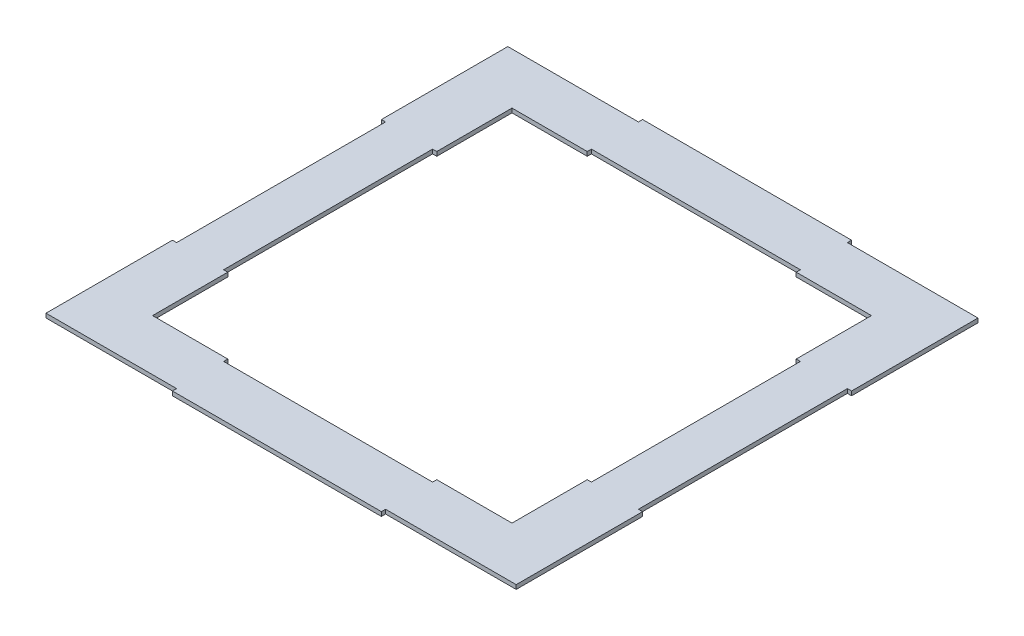
SolidWorks part; units mm, degrees
ref_plane "Front Plane" through (0, 0, 0) normal (0, 0, 1) x (1, 0, 0)
ref_plane "Top Plane" through (0, 0, 0) normal (0, 1, 0) x (1, 0, 0)
ref_plane "Right Plane" through (0, 0, 0) normal (1, 0, 0) x (0, 0, -1)
sketch "Sketch1" plane through (0, 0, 0) normal (0, 1, 0) x (1, 0, 0)
  line L0 (-225.2349, 99.8825) -> (-225.2349, 220.8825)
  line L1 (-100.2349, -225.1175) -> (99.7651, -225.1175)
  line L2 (-225.2349, -221.1175) -> (-225.2349, -100.1175)
  line L3 (-100.2349, 224.8825) -> (99.7651, 224.8825)
  line L4 (224.7651, -221.1175) -> (224.7651, -100.1175)
  line L6 (224.7651, -100.1175) -> (220.7651, -100.1175)
  line L7 (224.7651, 99.8825) -> (220.7651, 99.8825)
  line L8 (220.7651, -100.1175) -> (220.7651, 99.8825)
  line L9 (-100.2349, 224.8825) -> (99.7651, 224.8825)
  line L10 (-100.2349, 224.8825) -> (-100.2349, 220.8825)
  line L11 (99.7651, 224.8825) -> (99.7651, 220.8825)
  line L12 (-225.2349, 99.8825) -> (-221.2349, 99.8825)
  line L13 (-225.2349, -100.1175) -> (-221.2349, -100.1175)
  line L14 (-221.2349, 99.8825) -> (-221.2349, -100.1175)
  line L15 (-100.2349, -225.1175) -> (99.7651, -225.1175)
  line L16 (-100.2349, -225.1175) -> (-100.2349, -221.1175)
  line L17 (99.7651, -225.1175) -> (99.7651, -221.1175)
  line L18 (224.7651, 99.8825) -> (224.7651, 220.8825)
  line L19 (99.7651, 220.8825) -> (224.7651, 220.8825)
  line L20 (-100.2349, 220.8825) -> (-225.2349, 220.8825)
  line L21 (99.7651, -221.1175) -> (224.7651, -221.1175)
  line L22 (-100.2349, -221.1175) -> (-225.2349, -221.1175)
  line L24 (-172.2349, -172.1175) -> (-100.2349, -172.1175)
  line L25 (-172.2349, -172.1175) -> (-172.2349, -100.1175)
  line L26 (-172.2349, 171.8825) -> (-100.2349, 171.8825)
  line L27 (171.7651, -172.1175) -> (171.7651, -100.1175)
  line L28 (-172.2349, -172.1175) -> (171.7651, 171.8825) construction
  line L29 (-172.2349, 171.8825) -> (171.7651, -172.1175) construction
  line L31 (-172.2349, 99.8825) -> (-172.2349, 171.8825)
  line L32 (171.7651, 99.8825) -> (175.7651, 99.8825)
  line L34 (171.7651, -100.1175) -> (175.7651, -100.1175)
  line L35 (175.7651, 99.8825) -> (175.7651, -100.1175)
  line L37 (-100.2349, 171.8825) -> (-100.2349, 175.8825)
  line L38 (-100.2349, 175.8825) -> (99.7651, 175.8825)
  line L39 (99.7651, 171.8825) -> (99.7651, 175.8825)
  line L40 (-172.2349, 99.8825) -> (-176.2349, 99.8825)
  line L42 (-172.2349, -100.1175) -> (-176.2349, -100.1175)
  line L43 (-176.2349, 99.8825) -> (-176.2349, -100.1175)
  line L45 (-100.2349, -172.1175) -> (-100.2349, -176.1175)
  line L46 (-100.2349, -176.1175) -> (99.7651, -176.1175)
  line L47 (99.7651, -172.1175) -> (99.7651, -176.1175)
  line L48 (99.7651, -172.1175) -> (171.7651, -172.1175)
  line L49 (171.7651, 99.8825) -> (171.7651, 171.8825)
  line L50 (99.7651, 171.8825) -> (171.7651, 171.8825)
  point P0 (-0.2349, -0.1175)
  point P1 (-0.2349, -0.1175)
  point P2 (0, 0)
  dimension "D1" = 4
  dimension "D2" = 4
  dimension "D3" = 100
  dimension "D4" = 100
  dimension "D5" = 200
  dimension "D6" = 4
  dimension "D7" = 4
  dimension "D8" = 100
  dimension "D9" = 100
  dimension "D10" = 221
  dimension "D11" = 221
  dimension "D12" = 225
  dimension "D13" = 225
  dimension "D14" = 4
  dimension "D15" = 4
  dimension "D16" = 172
  dimension "D17" = 172
  dimension "D18" = 4
  dimension "D19" = 200
  dimension "D20" = 200
  dimension "D21" = 200
  dimension "D22" = 4
  dimension "D23" = 200
  dimension "D24" = 4
extrude "Boss-Extrude1" add sketch "Sketch1" along normal blind 4
